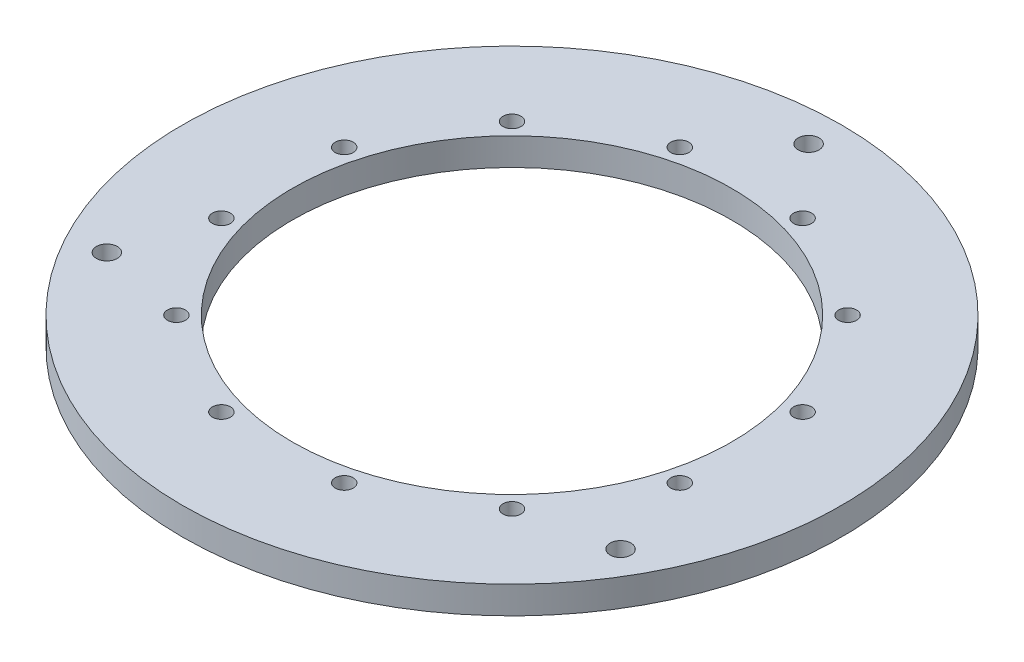
SolidWorks part; units mm, degrees
ref_plane "Front Plane" through (0, 0, 0) normal (0, 0, 1) x (1, 0, 0)
ref_plane "Top Plane" through (0, 0, 0) normal (0, 1, 0) x (1, 0, 0)
ref_plane "Right Plane" through (0, 0, 0) normal (1, 0, 0) x (0, 0, -1)
sketch "Sketch2" plane through (0, 0, 0) normal (0, 1, 0) x (1, 0, 0)
  line L0 (0, 0) -> (0, 76.2) construction
  line L1 (0, 0) -> (19.722, 73.6035) construction
  line L2 (0, 0) -> (14.1998, 52.9946) construction
  circle A0 centre (0, 0) radius 76.2
  circle A1 centre (0, 0) radius 50.8
  circle A2 centre (0, 68.58) radius 2.413
  circle A3 centre (59.392, -34.29) radius 2.413
  circle A4 centre (-59.392, -34.29) radius 2.413
  circle A5 centre (14.1998, 52.9946) radius 2.0828
  circle A6 centre (38.7947, 38.7947) radius 2.0828
  circle A7 centre (0, 0) radius 76.2
  circle A8 centre (52.9946, 14.1998) radius 2.0828
  circle A9 centre (0, 0) radius 76.2
  circle A10 centre (52.9946, -14.1998) radius 2.0828
  circle A11 centre (0, 0) radius 76.2
  circle A12 centre (38.7947, -38.7947) radius 2.0828
  circle A13 centre (0, 0) radius 76.2
  circle A14 centre (14.1998, -52.9946) radius 2.0828
  circle A15 centre (0, 0) radius 76.2
  circle A16 centre (-14.1998, -52.9946) radius 2.0828
  circle A17 centre (0, 0) radius 76.2
  circle A18 centre (-38.7947, -38.7947) radius 2.0828
  circle A19 centre (0, 0) radius 76.2
  circle A20 centre (-52.9946, -14.1998) radius 2.0828
  circle A21 centre (0, 0) radius 76.2
  circle A22 centre (-52.9946, 14.1998) radius 2.0828
  circle A23 centre (0, 0) radius 76.2
  circle A24 centre (-38.7947, 38.7947) radius 2.0828
  circle A25 centre (0, 0) radius 76.2
  circle A26 centre (-14.1998, 52.9946) radius 2.0828
  circle A27 centre (0, 0) radius 76.2
  point P12 (0, 0)
  dimension "D1" = 152.4
  dimension "D2" = 101.6
  dimension "D3" = 4.826
  dimension "D4" = 68.58
  dimension "D6" = 4.1656
  dimension "D7" = 15
  dimension "D10" = 54.864
  dimension "D5" = 3
  dimension "D9" = 12
extrude "Boss-Extrude1" add sketch "Sketch2" along normal blind 6.35 contours A0 A26 A24 A22 A20 A18 A16 A14 A12 A10 A8 A6 A5 A4 A3 A2 A1
